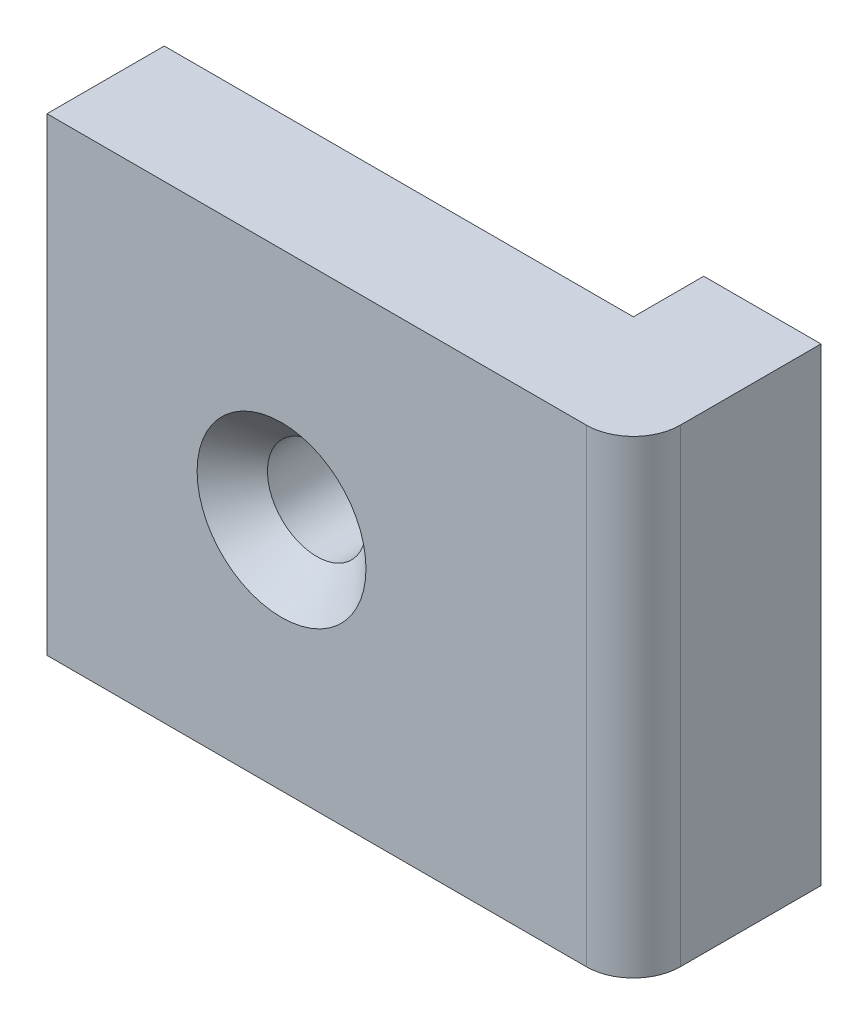
SolidWorks part; units mm, degrees
ref_plane "正面" through (0, 0, 0) normal (0, 0, 1) x (1, 0, 0)
ref_plane "平面" through (0, 0, 0) normal (0, 1, 0) x (1, 0, 0)
ref_plane "右側面" through (0, 0, 0) normal (1, 0, 0) x (0, 0, -1)
sketch "ｽｹｯﾁ2" plane through (0, 0, 0) normal (0, 0, 1) x (1, 0, 0)
  line L1 (-10, 10) -> (10, 10)
  line L2 (-10, 10) -> (-10, -10)
  line L3 (-10, -10) -> (10, -10)
  line L4 (10, 10) -> (10, -10)
  line L5 (-10, 10) -> (10, -10) construction
  line L6 (-10, -10) -> (10, 10) construction
  circle A0 centre (0, 0) radius 2.1
  point P0 (0, 0)
  dimension "D3" = 4.2
  dimension "D1" = 20
  dimension "D2" = 20
extrude "ﾎﾞｽ - 押し出し1" add sketch "ｽｹｯﾁ2" along normal blind 5
sketch "ｽｹｯﾁ3" plane through (10, 0, 0) normal (1, 0, 0) x (0, 0, -1)
  line L0 (-5, -10) -> (0, -10) construction
  line L1 (-5, 10) -> (3, 10)
  line L2 (-5, 10) -> (-5, -10)
  line L3 (-5, -10) -> (3, -10)
  line L4 (3, 10) -> (3, -10)
  dimension "D1" = 8
extrude "ﾎﾞｽ - 押し出し2" add sketch "ｽｹｯﾁ3" along normal blind 5
fillet "ﾌｨﾚｯﾄ2" radius 2 1 edges at (15, 0, 5)
sketch "ｽｹｯﾁ4" plane through (0, 0, 0) normal (0, 0, -1) x (-1, 0, 0)
  line L0 (0, 0) -> (-10, 0) construction
  line L1 (-10, -10) -> (-10, 10) construction
  line L3 (-7, -2.75) -> (-10, -2.75)
  line L4 (-7, -2.75) -> (-7, 2.75)
  line L5 (-7, 2.75) -> (-10, 2.75)
  line L6 (-10, -2.75) -> (-10, 2.75)
  line L7 (-7, -2.75) -> (-10, 2.75) construction
  line L8 (-7, 2.75) -> (-10, -2.75) construction
  point P5 (-8.5, 0)
  dimension "D1" = 5.5
  dimension "D2" = 3
extrude "ﾎﾞｽ - 押し出し3" add sketch "ｽｹｯﾁ4" along normal up to surface (3 mm away) up to face at (12.5, 0, -3)
chamfer "面取り1" distance 1.5 angle 45 1 edges at (2.1, 0, 5)
